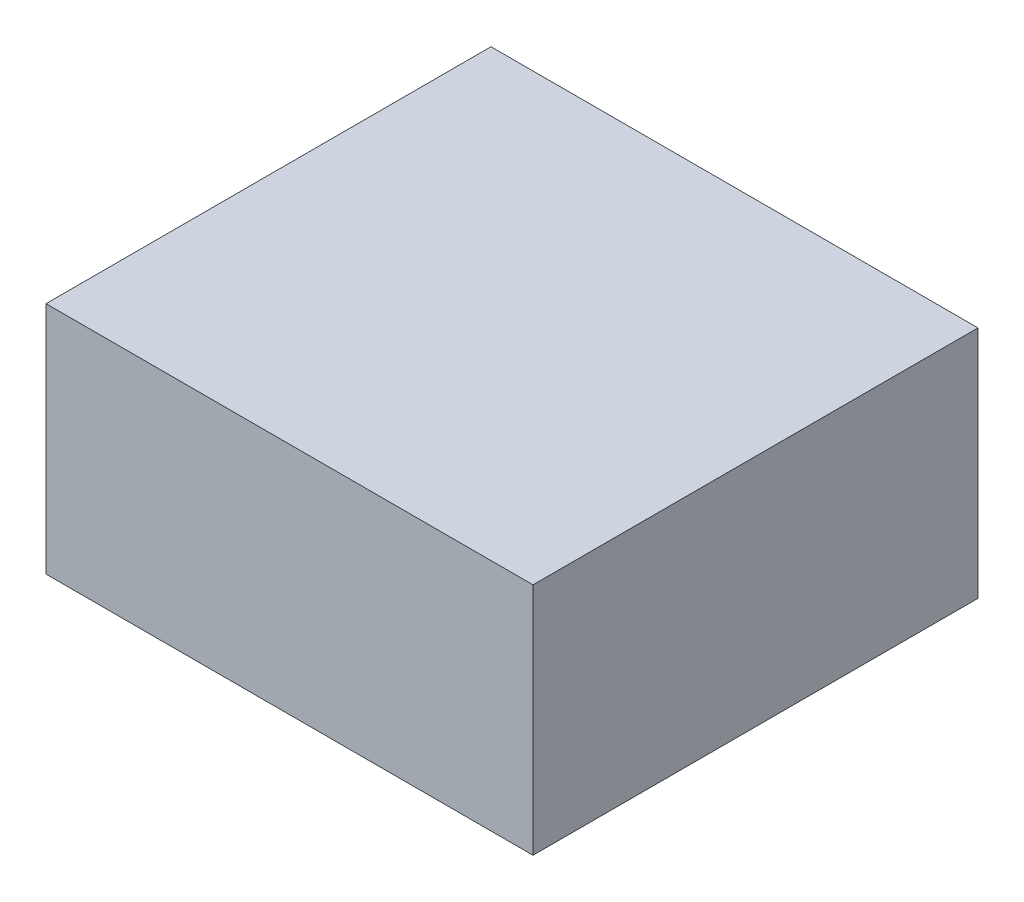
SolidWorks part; units mm, degrees
ref_plane "Front Plane" through (0, 0, 0) normal (0, 0, 1) x (1, 0, 0)
ref_plane "Top Plane" through (0, 0, 0) normal (0, 1, 0) x (1, 0, 0)
ref_plane "Right Plane" through (0, 0, 0) normal (1, 0, 0) x (0, 0, -1)
sketch "Sketch1" plane through (0, 0, 0) normal (0, 1, 0) x (1, 0, 0)
  line L1 (0, 0) -> (60.3, 0)
  line L2 (0, 0) -> (0, -55.1)
  line L3 (0, -55.1) -> (60.3, -55.1)
  line L4 (60.3, 0) -> (60.3, -55.1)
  dimension "D1" = 60.3
  dimension "D2" = 55.1
extrude "Boss-Extrude1" add sketch "Sketch1" along normal blind 29
